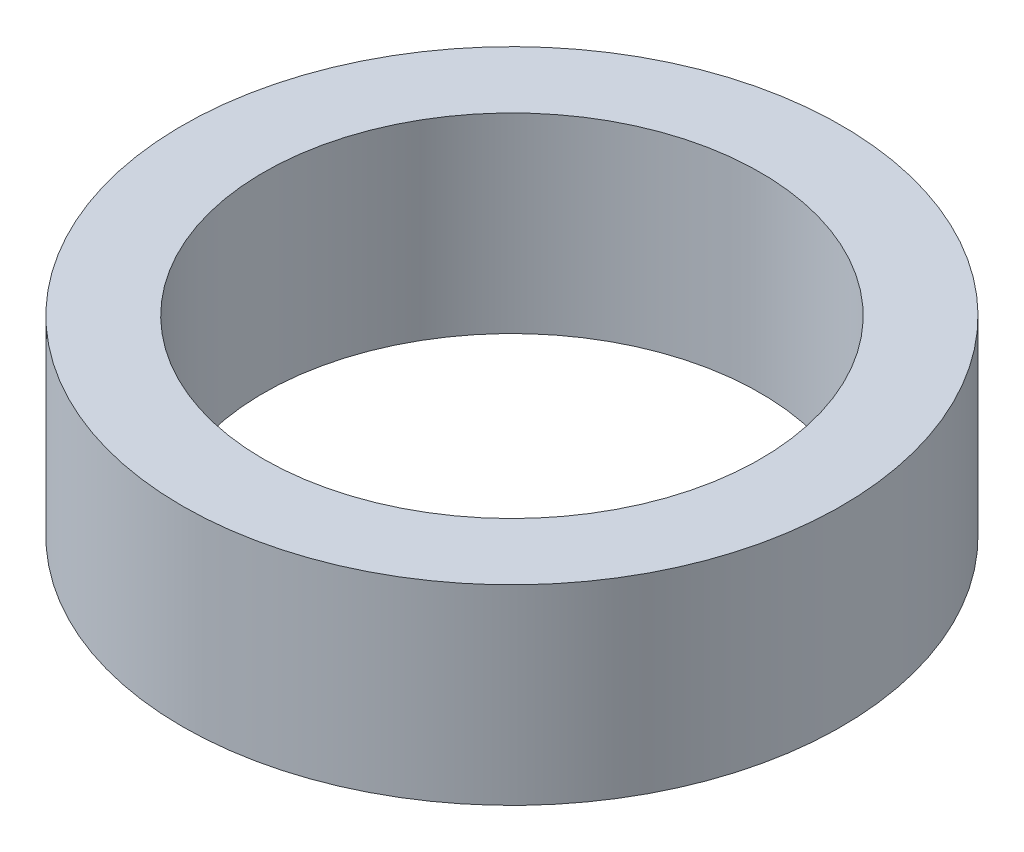
SolidWorks part; units mm, degrees
ref_plane "Front Plane" through (0, 0, 0) normal (0, 0, 1) x (1, 0, 0)
ref_plane "Top Plane" through (0, 0, 0) normal (0, 1, 0) x (1, 0, 0)
ref_plane "Right Plane" through (0, 0, 0) normal (1, 0, 0) x (0, 0, -1)
sketch "Sketch1" plane through (0, 0, 0) normal (0, 1, 0) x (1, 0, 0)
  circle A0 centre (0, 0) radius 2.6
  circle A1 centre (0, 0) radius 3.45
  dimension "D1" = 5.2
  dimension "D2" = 6.9
extrude "Boss-Extrude1" add sketch "Sketch1" along normal blind 2
